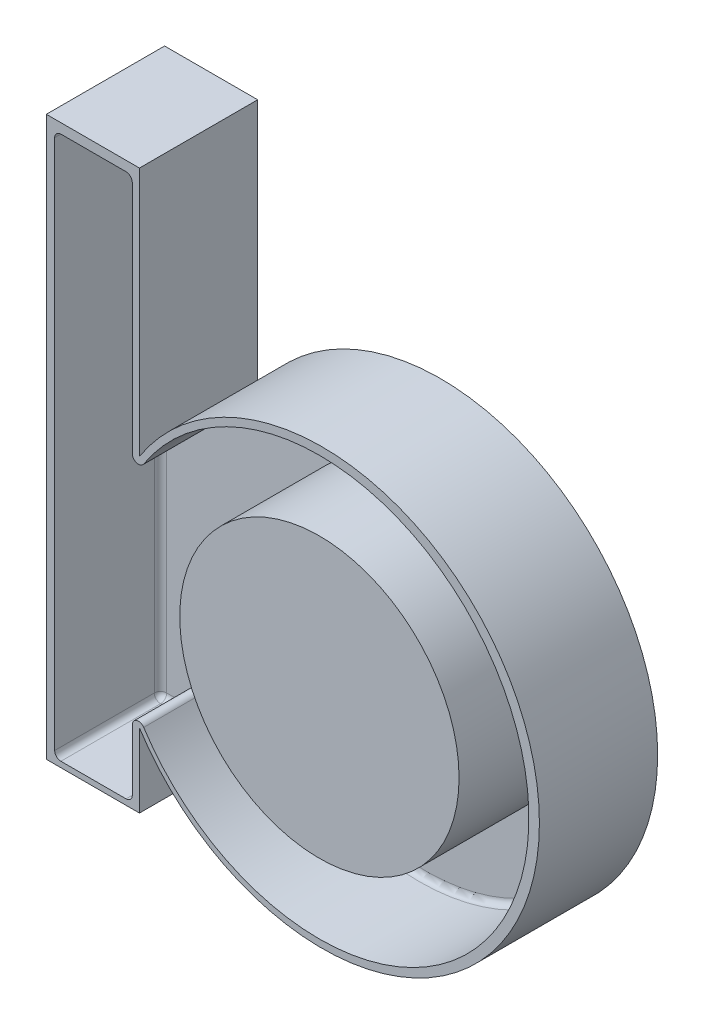
SolidWorks part; units mm, degrees
ref_plane "Alzado" through (0, 0, 0) normal (0, 0, 1) x (1, 0, 0)
ref_plane "Planta" through (0, 0, 0) normal (0, 1, 0) x (1, 0, 0)
ref_plane "Vista lateral" through (0, 0, 0) normal (1, 0, 0) x (0, 0, -1)
sketch "Sketch1" plane through (0, 0, 0) normal (0, 0, 1) x (1, 0, 0)
  line L0 (0, 0) -> (100, 0) construction
  line L1 (100, 0) -> (100, 100) construction
  line L2 (100, 100) -> (0, 100) construction
  line L3 (0, 100) -> (0, 0) construction
  line L5 (14.6419, 96.1168) -> (29.6419, 96.1168)
  line L6 (14.6419, 96.1168) -> (14.6419, 6.1168)
  line L7 (14.6419, 6.1168) -> (29.6419, 6.1168)
  line L8 (29.6419, 96.1168) -> (29.6419, 55.8784)
  line L12 (29.6419, 18.0092) -> (29.6419, 6.1168)
  arc A0 (29.6419, 18.0092) -> (29.6419, 55.8784) centre (59.078, 36.9438) ccw
  point P3 (22.8527, 50)
  point P12 (59.078, 36.9438)
  dimension "D3" = 70
  dimension "D4" = 90
  dimension "D1" = 100
  dimension "D2" = 100
  dimension "D5" = 15
extrude "Boss-Extrude1" add sketch "Sketch1" along normal blind 19.05
sketch "Sketch4" plane through (0, 0, 19.05) normal (0, 0, 1) x (1, 0, 0)
  line L0 (28.4863, 21.6192) -> (28.4863, 7.0233)
  line L1 (15.9863, 94.5233) -> (28.4863, 94.5233)
  line L2 (15.9863, 94.5233) -> (15.9863, 7.0233)
  line L3 (15.9863, 7.0233) -> (28.4863, 7.0233)
  line L4 (28.4863, 94.5233) -> (28.4863, 51.9626)
  arc A1 (28.4863, 21.6192) -> (28.4863, 51.9626) centre (58.634, 36.7909) ccw
  circle A2 centre (58.634, 36.7909) radius 22.5
  point P2 (22.2363, 50.7733)
  dimension "D1" = 45
  dimension "D4" = 67.5
  dimension "D2" = 12.5
  dimension "D3" = 87.5
extrude "Cut-Extrude1" cut sketch "Sketch4" against normal blind 17.05
fillet "Fillet1" radius 1 11 edges at (28.4863, 21.6192, 10.525) (28.4863, 51.9626, 10.525) (28.4863, 14.3213, 2) (92.384, 36.7909, 2) (28.4863, 73.243, 2) (15.9863, 50.7733, 2) (22.2363, 7.0233, 2) (28.4863, 7.0233, 10.525) (15.9863, 7.0233, 10.525) (15.9863, 94.5233, 10.525) (28.4863, 94.5233, 10.525)
